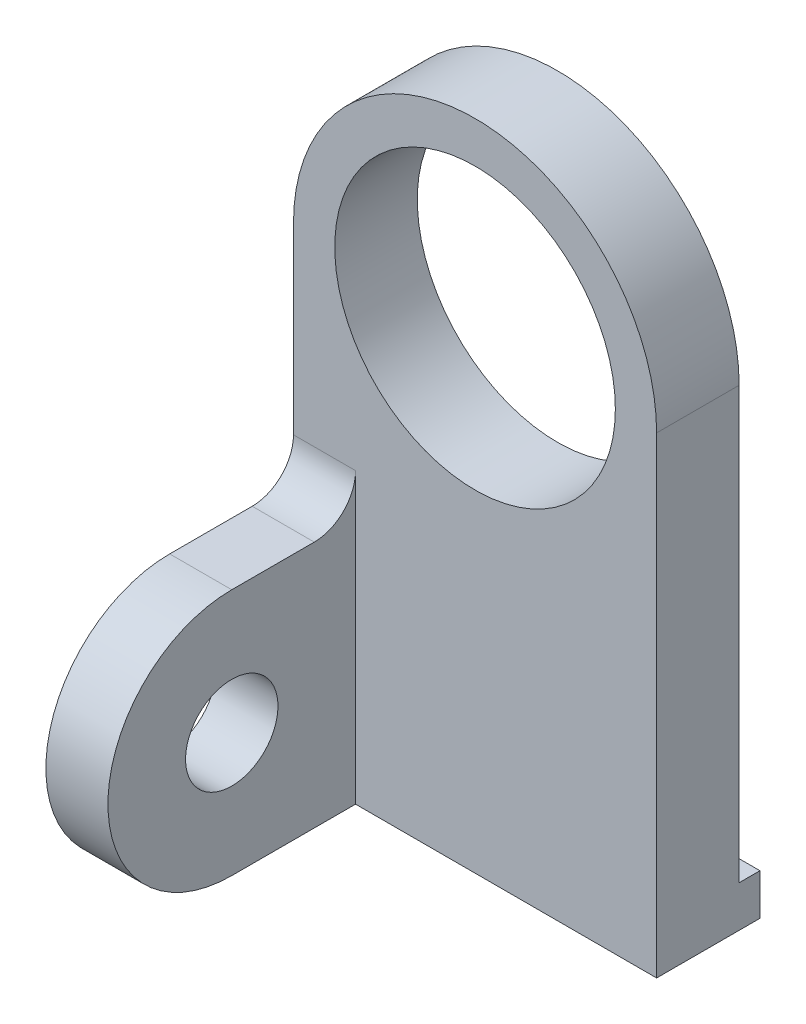
SolidWorks part; units mm, degrees
ref_plane "Front Plane" through (0, 0, 0) normal (0, 0, 1) x (1, 0, 0)
ref_plane "Top Plane" through (0, 0, 0) normal (0, 1, 0) x (1, 0, 0)
ref_plane "Right Plane" through (0, 0, 0) normal (1, 0, 0) x (0, 0, -1)
sketch "Sketch2" plane through (0, 0, 0) normal (0, 0, 1) x (1, 0, 0)
  line L0 (-13.97, 0) -> (-13.97, -33.147)
  line L1 (-13.97, -33.147) -> (13.97, -33.147)
  line L2 (13.97, 0) -> (13.97, -33.147)
  circle A0 centre (0, 0) radius 10.795
  arc A1 (13.97, 0) -> (-13.97, 0) centre (0, 0) ccw
  circle A2 centre (0, 0) radius 13.97 construction
  dimension "D1" = 21.59
  dimension "D3" = 33.147
  dimension "D2" = 3.175
extrude "Boss-Extrude1" add sketch "Sketch2" along normal blind 6.35
sketch "Sketch4" plane through (0, 0, 6.35) normal (0, 0, 1) x (1, 0, 0)
  line L1 (-13.97, -33.147) -> (13.97, -33.147)
  line L2 (-13.97, -33.147) -> (-13.97, -36.322)
  line L3 (-13.97, -36.322) -> (13.97, -36.322)
  line L4 (13.97, -33.147) -> (13.97, -36.322)
  dimension "D1" = 3.175
extrude "Boss-Extrude2" add sketch "Sketch4" against normal blind 7.9502
sketch "Sketch5" plane through (-13.97, 0, 0) normal (-1, 0, 0) x (0, 0, 1)
  line L0 (6.35, 0) -> (6.35, -36.322) construction
  line L1 (-1.6002, -36.322) -> (6.35, -36.322) construction
  line L2 (6.35, -36.322) -> (15.875, -36.322)
  line L3 (15.875, -17.272) -> (6.35, -17.272)
  line L4 (6.35, -17.272) -> (6.35, -36.322)
  arc A0 (15.875, -36.322) -> (15.875, -17.272) centre (15.875, -26.797) ccw
  circle A1 centre (15.875, -26.797) radius 3.556
  dimension "D1" = 19.05
  dimension "D3" = 7.112
  dimension "D2" = 9.525
extrude "Boss-Extrude3" add sketch "Sketch5" against normal blind 4.7752
fillet "Fillet2" radius 3.175 1 edges at (-11.5824, -17.272, 6.35)
